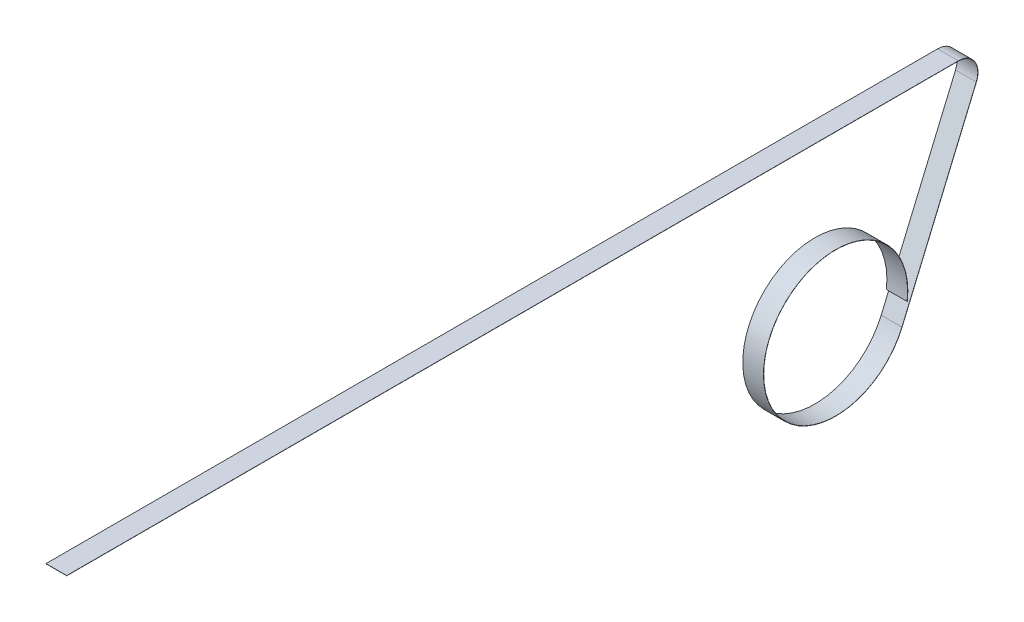
SolidWorks part; units mm, degrees
ref_plane "Front Plane" through (0, 0, 0) normal (0, 0, 1) x (1, 0, 0)
ref_plane "Top Plane" through (0, 0, 0) normal (0, 1, 0) x (1, 0, 0)
ref_plane "Right Plane" through (0, 0, 0) normal (1, 0, 0) x (0, 0, -1)
sketch "Sketch1" plane through (0, 0, 0) normal (0, 0, 1) x (1, 0, 0)
  line L1 (0, 0) -> (25.4, 0)
  line L2 (0, 0) -> (0, 0.254)
  line L3 (0, 0.254) -> (25.4, 0.254)
  line L4 (25.4, 0) -> (25.4, 0.254)
  dimension "D1" = 0.254
  dimension "D2" = 25.4
extrude "Boss-Extrude1" add sketch "Sketch1" along normal blind 1091.946 contours L3 L4 L1 L2
sketch "Sketch2" plane through (25.4, 0, 0) normal (1, 0, 0) x (0, 0, -1)
  line L3 (21.9782, -33.2045) -> (-69.0535, -247.6787)
  line L4 (22.212, -33.3037) -> (-68.8197, -247.7779)
  line L5 (-62.6617, -223.6289) -> (-62.4152, -223.7071)
  line L6 (0, 0) -> (0, 0.254)
  arc A0 (21.9782, -33.2045) -> (0, 0) centre (0, -23.876) ccw
  arc A1 (22.212, -33.3037) -> (0, 0.254) centre (0, -23.876) ccw
  arc A2 (-62.6617, -223.6289) -> (-69.0535, -247.6787) centre (-150.1945, -213.2391) ccw
  arc A3 (-62.4152, -223.7071) -> (-68.8197, -247.7779) centre (-150.1945, -213.2391) ccw
extrude "Boss-Extrude4" add sketch "Sketch2" against normal blind 25.4
